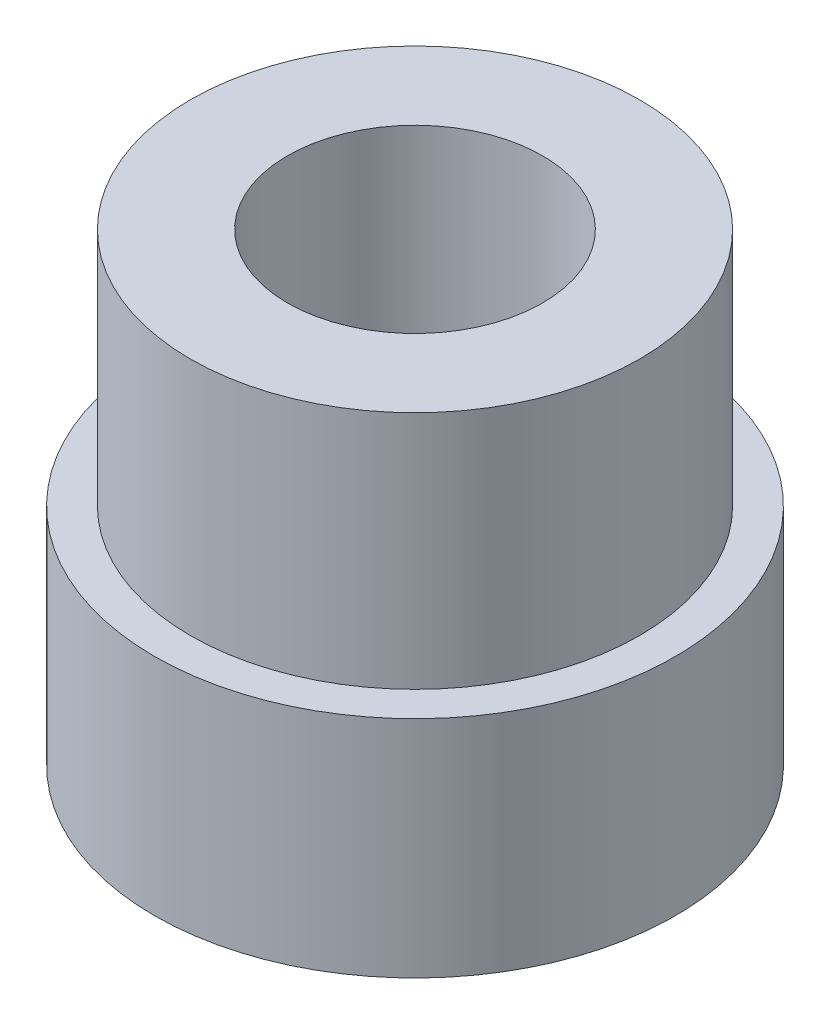
SolidWorks part; units mm, degrees
ref_plane "Front Plane" through (0, 0, 0) normal (0, 0, 1) x (1, 0, 0)
ref_plane "Top Plane" through (0, 0, 0) normal (0, 1, 0) x (1, 0, 0)
ref_plane "Right Plane" through (0, 0, 0) normal (1, 0, 0) x (0, 0, -1)
sketch "Sketch1" plane through (0, 0, 0) normal (0, 1, 0) x (1, 0, 0)
  circle A0 centre (0, 0) radius 5.5245
  dimension "D1" = 11.049
extrude "Boss-Extrude1" add sketch "Sketch1" along normal blind 4.7625
sketch "Sketch2" plane through (0, 4.7625, 0) normal (0, 1, 0) x (1, 0, 0)
  circle A0 centre (0, 0) radius 4.7625
  dimension "D1" = 9.525
extrude "Boss-Extrude2" add sketch "Sketch2" along normal blind 5.08
sketch "Sketch3" plane through (0, 9.8425, 0) normal (0, 1, 0) x (1, 0, 0)
  circle A0 centre (0, 0) radius 2.7051
  dimension "D1" = 5.4102
extrude "Cut-Extrude1" cut sketch "Sketch3" against normal through all
